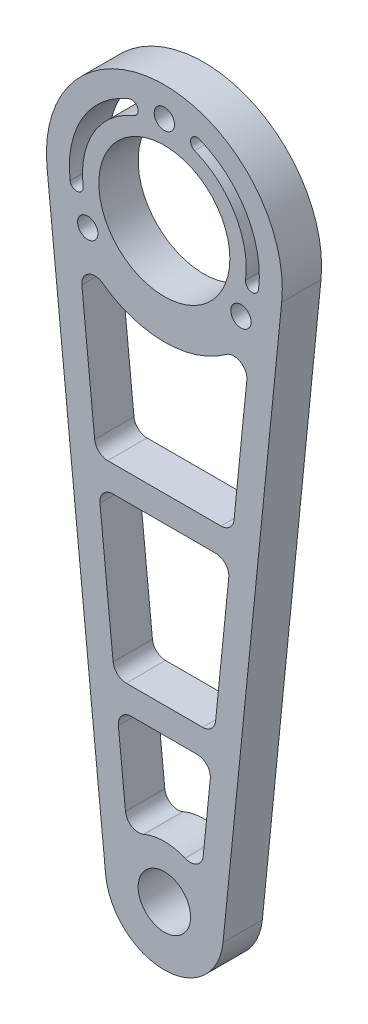
SolidWorks part; units mm, degrees
material "Thornel Mat VMA"
ref_plane "前视基准面" through (0, 0, 0) normal (0, 0, 1) x (1, 0, 0)
ref_plane "上视基准面" through (0, 0, 0) normal (0, 1, 0) x (1, 0, 0)
ref_plane "右视基准面" through (0, 0, 0) normal (1, 0, 0) x (0, 0, -1)
sketch "草图1" plane through (0, 0, 0) normal (0, 0, 1) x (1, 0, 0)
  line L0 (0, 0) -> (0, -61397.9139) construction
  line L1 (-17.9098, -1.8) -> (-8.9549, -90.9)
  line L2 (17.9098, -1.8) -> (8.9549, -90.9)
  circle A0 centre (0, 0) radius 18
  circle A1 centre (0, -90) radius 4
  circle A2 centre (0, 0) radius 10
  circle A3 centre (0, -90) radius 9
  circle A4 centre (0, 0) radius 13.5 construction
  circle A5 centre (0, 13.5) radius 1.55
  circle A6 centre (11.6913, -6.75) radius 1.55
  circle A7 centre (-11.6913, -6.75) radius 1.55
  point P22 (0, 0)
  dimension "D1" = 36
  dimension "D2" = 20
  dimension "D3" = 8
  dimension "D5" = 18
  dimension "D6" = 3.1
  dimension "D7" = 27
  dimension "D4" = 90
  dimension "D8" = 3
extrude "凸台-拉伸1" add sketch "草图1" along normal blind 6 contours A0 L0 A3 L2 | L0 A0 L1 A3 | L0 A0 A2 | A0 L0 A2 | L0 A3 A1 | A3 L0 A1
sketch "草图2" plane through (0, 0, 6) normal (0, 0, 1) x (1, 0, 0)
  line L0 (-13.1552, -9.1071) -> (-5.5994, -84.2863)
  line L1 (0, 0) -> (0, -50000) construction
  line L2 (-17.9098, -1.8) -> (-8.9549, -90.9) construction
  line L3 (13.1552, -9.1071) -> (5.5994, -84.2863)
  circle A0 centre (0, 0) radius 16
  circle A1 centre (0, -90) radius 8
  dimension "D1" = 32
  dimension "D2" = 16
  dimension "D3" = 4
extrude "切除-拉伸1" cut sketch "草图2" against normal blind 6 contours A0 L1 A1 L3 | L1 A0 L0 A1
sketch "草图3" plane through (0, 0, 6) normal (0, 0, 1) x (1, 0, 0)
  line L0 (-10.2514, -38) -> (10.2514, -38)
  line L1 (-13.1552, -9.1071) -> (-5.5994, -84.2863) construction
  line L2 (13.1552, -9.1071) -> (5.5994, -84.2863) construction
  line L3 (-7.4373, -66) -> (7.4373, -66)
  line L4 (-13.077, -36) -> (-13.077, -40)
  line L5 (-13.077, -40) -> (12.4013, -40)
  line L6 (12.4013, -40) -> (12.4013, -36)
  line L7 (12.4013, -36) -> (-13.077, -36)
  line L8 (-10.9724, -64) -> (-10.1843, -68)
  line L9 (-10.1843, -68) -> (10.9724, -68)
  line L10 (10.9724, -68) -> (10.1843, -64)
  line L11 (10.1843, -64) -> (-10.9724, -64)
  line M13 (-5.5994, -84.2863) -> (-13.1552, -9.1071)
  line M15 (13.1552, -9.1071) -> (5.5994, -84.2863)
  dimension "D1" = 38
  dimension "D2" = 28
  dimension "D3" = 2
  dimension "D4" = 2
  dimension "D5" = 2
  dimension "D6" = 2
extrude "凸台-拉伸2" add sketch "草图3" against normal up to surface (6 mm away) contours L5 L0 M13 M15 | L7 L0 M15 M13 | L9 L3 M13 M15 | L11 L3 M15 M13 up to face at (4, -90, 0)
fillet "圆角1" radius 2 12 edges at (5.5994, -84.2863, 3) (-5.5994, -84.2863, 3) (-7.2363, -68, 3) (7.2363, -68, 3) (-10.4524, -36, 3) (13.1552, -9.1071, 3) (10.4524, -36, 3) (-7.6383, -64, 3) (-10.0504, -40, 3) (10.0504, -40, 3) (7.6383, -64, 3) (-13.1552, -9.1071, 3)
sketch "草图4" plane through (0, 0, 6) normal (0, 0, 1) x (1, 0, 0)
  line L0 (0, 0) -> (0, 50000) construction
  arc A3 (-4.6296, 11.6111) -> (-5.3704, 13.4688) centre (-5, 12.5399) ccw
  arc A4 (-14.3777, -1.8796) -> (-12.3945, -1.6204) centre (-13.3861, -1.75) ccw
  circle A5 centre (-11.6913, -6.75) radius 1.55 construction
  arc A6 (-4.6296, 11.6111) -> (-12.3945, -1.6204) centre (0, 0) ccw
  arc A7 (-4.058, 12.8756) -> (-13.2198, -2.7361) centre (0, 0) ccw construction
  arc A8 (-5.3704, 13.4688) -> (-14.3777, -1.8796) centre (0, 0) ccw
  arc A9 (4.058, 12.8756) -> (13.2198, -2.7361) centre (0, 0) cw construction
  arc A10 (5.3704, 13.4688) -> (14.3777, -1.8796) centre (0, 0) cw
  arc A11 (4.6296, 11.6111) -> (12.3945, -1.6204) centre (0, 0) cw
  arc A12 (14.3777, -1.8796) -> (12.3945, -1.6204) centre (13.3861, -1.75) cw
  arc A13 (4.6296, 11.6111) -> (5.3704, 13.4688) centre (5, 12.5399) cw
  dimension "D1" = 14.5
  dimension "D2" = 12.5
  dimension "D5" = 1
  dimension "D6" = 13.5
  dimension "D7" = 1
  dimension "D3" = 5
  dimension "D4" = 5
extrude "切除-拉伸2" cut sketch "草图4" against normal blind 10
